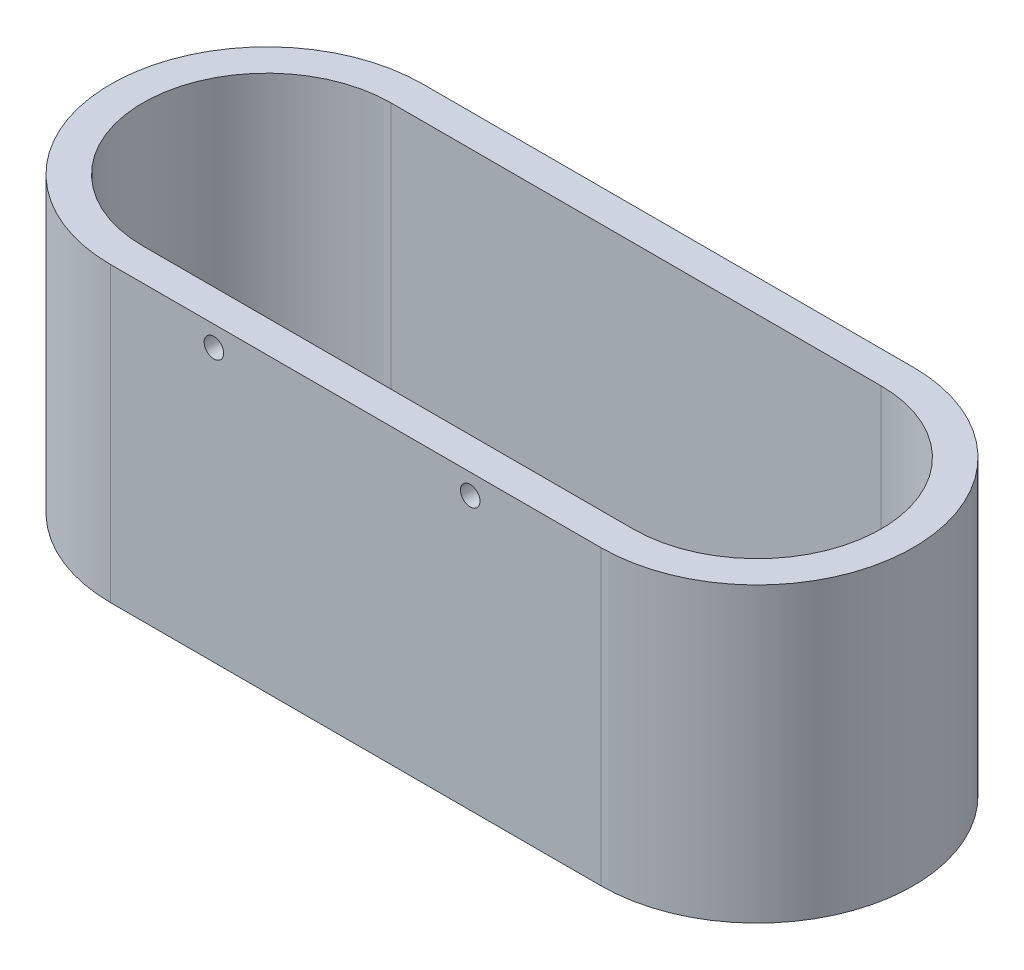
SolidWorks part; units mm, degrees
ref_plane "Front Plane" through (0, 0, 0) normal (0, 0, 1) x (1, 0, 0)
ref_plane "Top Plane" through (0, 0, 0) normal (0, 1, 0) x (1, 0, 0)
ref_plane "Right Plane" through (0, 0, 0) normal (1, 0, 0) x (0, 0, -1)
sketch "Sketch1" plane through (0, 0, 0) normal (0, 1, 0) x (1, 0, 0)
  line L0 (-37.5, 0) -> (37.5, 0) construction
  line L1 (0, -12.7) -> (0, 12.7) construction
  line L2 (-25.8382, 12.7) -> (24.3852, 12.7)
  line L3 (-25.8382, -12.7) -> (24.3852, -12.7)
  line L4 (-25.8382, 16) -> (24.3852, 16)
  line L5 (-25.8382, -16) -> (24.3852, -16)
  circle A0 centre (-25.8382, 0) radius 12.7
  circle A1 centre (24.3852, 0) radius 12.7
  circle A2 centre (-25.8382, 0) radius 16
  circle A3 centre (24.3852, 0) radius 16
  point P4 (0, 0)
  point P8 (0, 0)
extrude "Boss-Extrude1" add sketch "Sketch1" along normal blind 30 contours A3 L3 A2 L5 | A2 L3 A0 L2 | A3 L4 A2 L2 | A3 L2 A1 L3
sketch "Sketch2" plane through (0, 0, 16) normal (0, 0, 1) x (1, 0, 0)
  circle A0 centre (-15.2613, 27.915) radius 1
  circle A1 centre (10.9965, 27.915) radius 1
  point P4 (0, 0)
  point P5 (10.9965, 27.915)
extrude "Cut-Extrude1" cut sketch "Sketch2" against normal up to next
